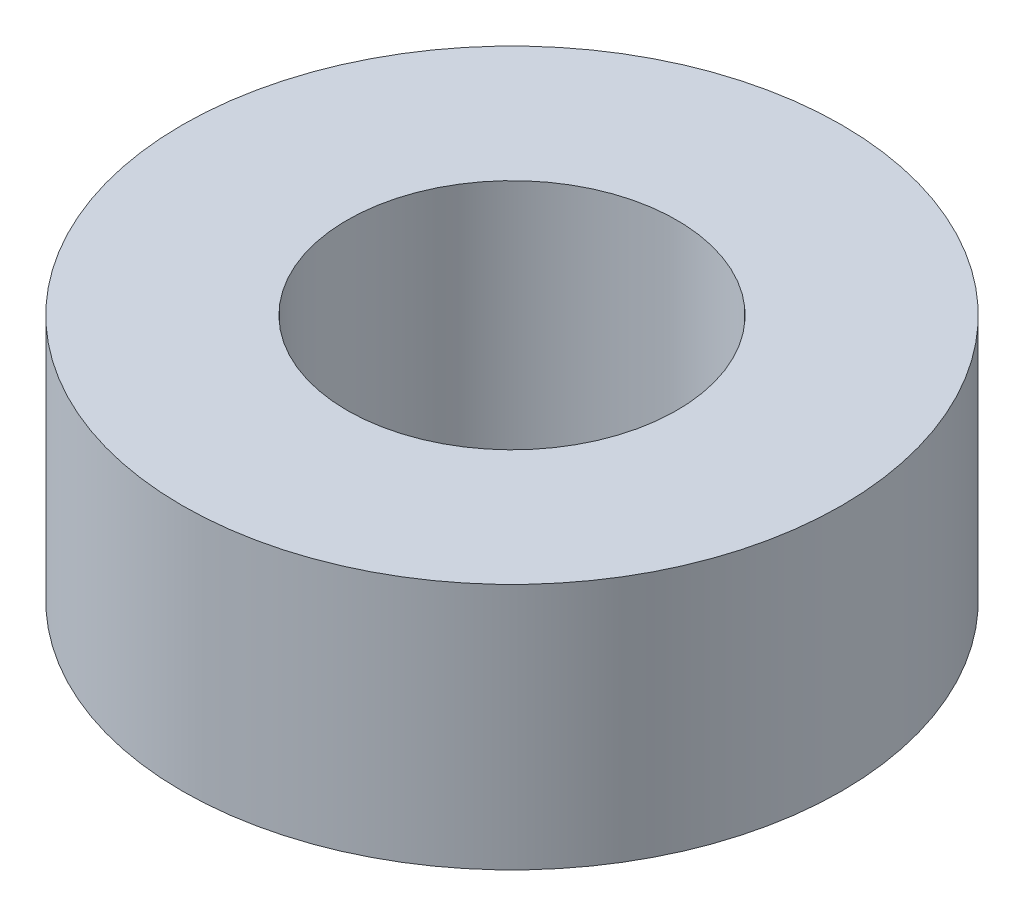
SolidWorks part; units mm, degrees
ref_plane "Front Plane" through (0, 0, 0) normal (0, 0, 1) x (1, 0, 0)
ref_plane "Top Plane" through (0, 0, 0) normal (0, 1, 0) x (1, 0, 0)
ref_plane "Right Plane" through (0, 0, 0) normal (1, 0, 0) x (0, 0, -1)
sketch "Sketch2" plane through (0, 0, 0) normal (0, 1, 0) x (1, 0, 0)
  circle A0 centre (0, 0) radius 2
  circle A1 centre (0, 0) radius 4
  dimension "D1" = 8
  dimension "D2" = 4
extrude "Boss-Extrude1" add sketch "Sketch2" along normal blind 3
